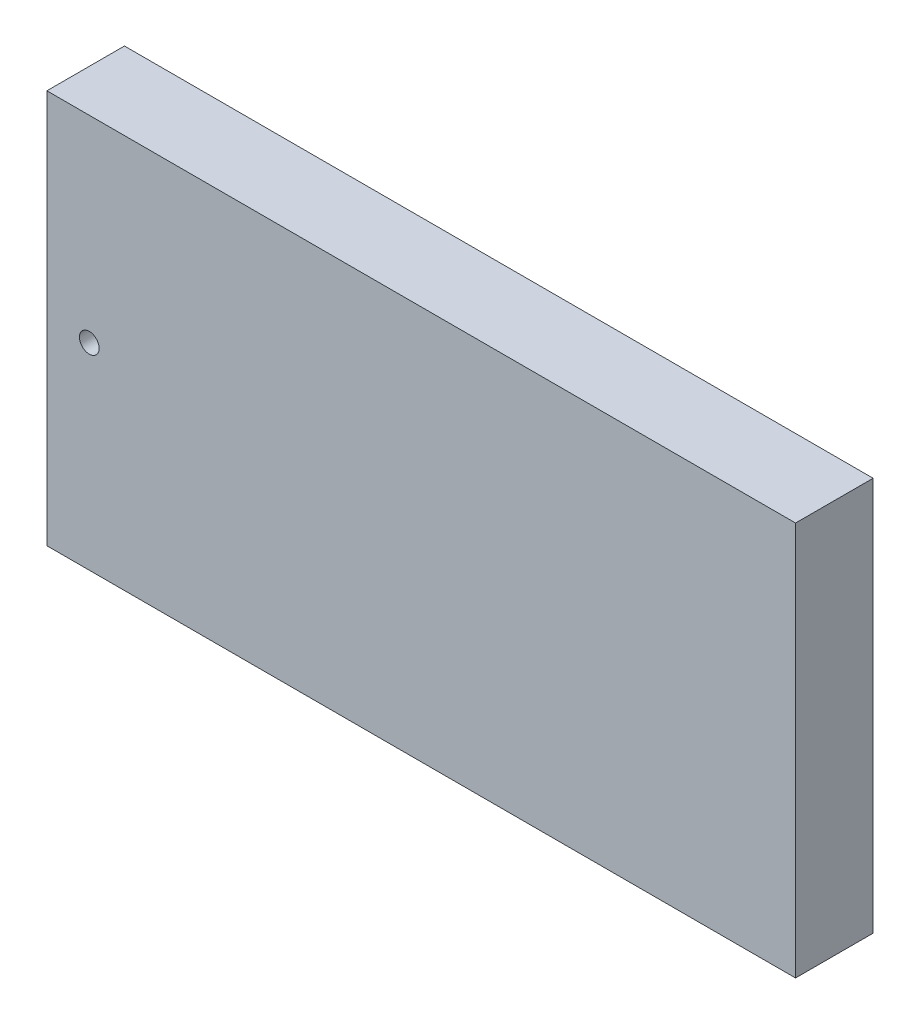
SolidWorks part; units mm, degrees
ref_plane "Front Plane" through (0, 0, 0) normal (0, 0, 1) x (1, 0, 0)
ref_plane "Top Plane" through (0, 0, 0) normal (0, 1, 0) x (1, 0, 0)
ref_plane "Right Plane" through (0, 0, 0) normal (1, 0, 0) x (0, 0, -1)
sketch "Sketch1" plane through (0, 0, 0) normal (0, 0, 1) x (1, 0, 0)
  line L1 (-482.6, -254) -> (482.6, -254)
  line L2 (-482.6, -254) -> (-482.6, 254)
  line L3 (-482.6, 254) -> (482.6, 254)
  line L4 (482.6, -254) -> (482.6, 254)
  line L5 (-482.6, -254) -> (482.6, 254) construction
  line L6 (-482.6, 254) -> (482.6, -254) construction
  point P0 (0, 0)
  dimension "D1" = 508
  dimension "D2" = 965.2
extrude "Boss-Extrude1" add sketch "Sketch1" against normal blind 100
sketch "Sketch2" plane through (0, 0, 0) normal (0, 0, 1) x (1, 0, 0)
  circle A0 centre (-427.9565, 0) radius 12.7
  dimension "D1" = 25.4
extrude "Cut-Extrude1" cut sketch "Sketch2" against normal through all both contours A0
